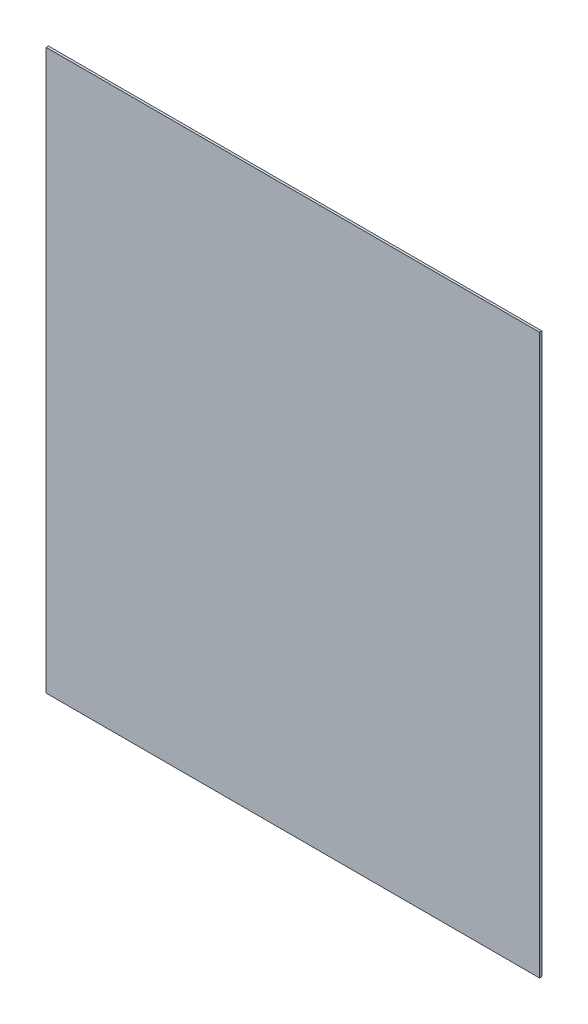
SolidWorks part; units mm, degrees
ref_plane "Front" through (0, 0, 0) normal (0, 0, 1) x (1, 0, 0)
ref_plane "Top" through (0, 0, 0) normal (0, 1, 0) x (1, 0, 0)
ref_plane "Right" through (0, 0, 0) normal (1, 0, 0) x (0, 0, -1)
sketch "Sketch1" plane through (0, 0, 0) normal (0, 0, 1) x (1, 0, 0)
  line L1 (-266.7, -302.26) -> (266.7, -302.26)
  line L2 (-266.7, -302.26) -> (-266.7, 302.26)
  line L3 (-266.7, 302.26) -> (266.7, 302.26)
  line L4 (266.7, -302.26) -> (266.7, 302.26)
  line L5 (-266.7, -302.26) -> (266.7, 302.26) construction
  line L6 (-266.7, 302.26) -> (266.7, -302.26) construction
  point P0 (0, 0)
  dimension "D1" = 533.4
  dimension "D2" = 604.52
extrude "Boss-Extrude1" add sketch "Sketch1" along normal blind 2.54
